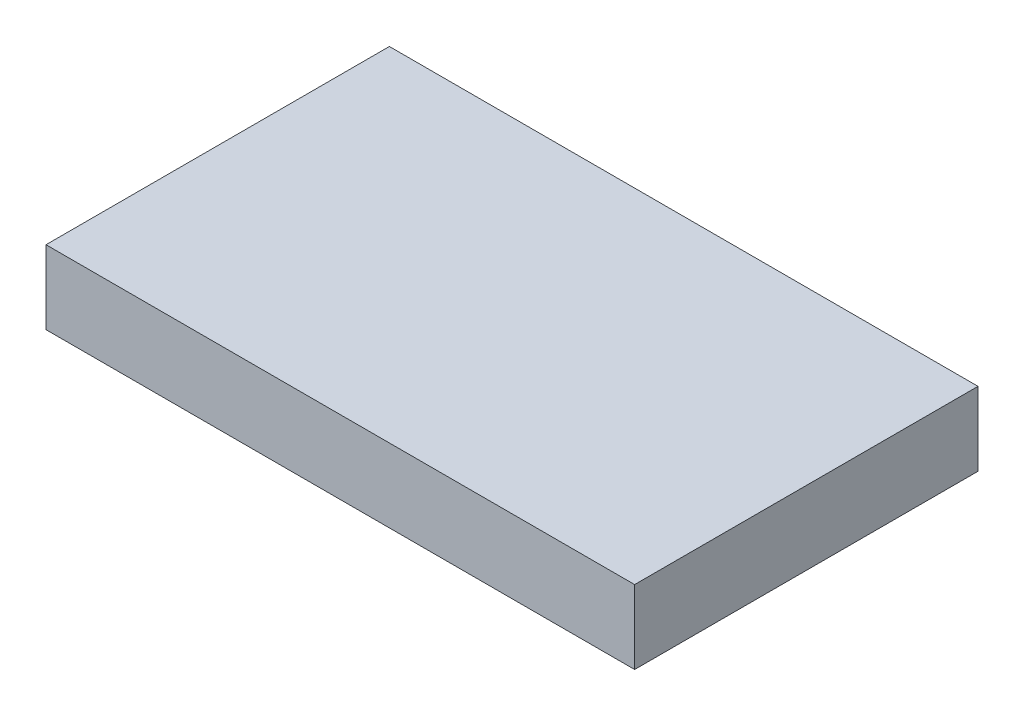
SolidWorks part; units mm, degrees
ref_plane "Front Plane" through (0, 0, 0) normal (0, 0, 1) x (1, 0, 0)
ref_plane "Top Plane" through (0, 0, 0) normal (0, 1, 0) x (1, 0, 0)
ref_plane "Right Plane" through (0, 0, 0) normal (1, 0, 0) x (0, 0, -1)
sketch "Sketch1" plane through (0, 0, 0) normal (0, 1, 0) x (1, 0, 0)
  line L1 (0, 0) -> (76.2, 0)
  line L2 (0, 0) -> (0, 44.45)
  line L3 (0, 44.45) -> (76.2, 44.45)
  line L4 (76.2, 0) -> (76.2, 44.45)
  dimension "D1" = 76.2
  dimension "D2" = 44.45
extrude "Boss-Extrude1" add sketch "Sketch1" along normal blind 9.525
sketch "Sketch2" plane through (0, 9.525, 0) normal (0, 1, 0) x (1, 0, 0)
  line L0 (0, 22.225) -> (76.2, 22.225) construction
  line L1 (0, 44.45) -> (0, 0) construction
  line L2 (76.2, 0) -> (76.2, 44.45) construction
